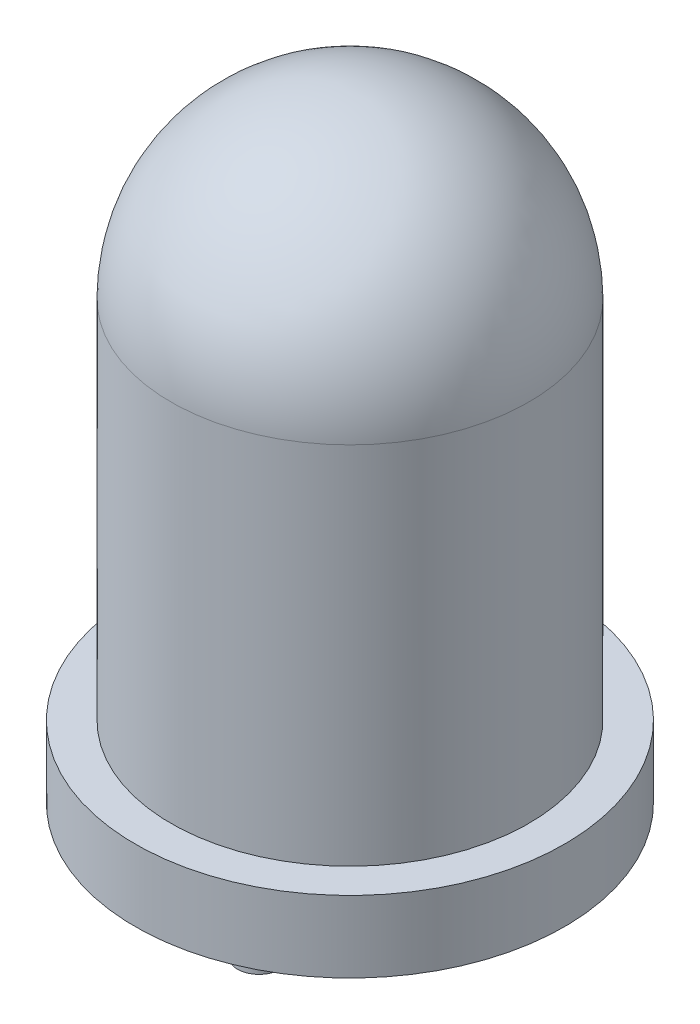
SolidWorks part; units mm, degrees
ref_plane "Plan de face" through (0, 0, 0) normal (0, 0, 1) x (1, 0, 0)
ref_plane "Plan de dessus" through (0, 0, 0) normal (0, 1, 0) x (1, 0, 0)
ref_plane "Plan de droite" through (0, 0, 0) normal (1, 0, 0) x (0, 0, -1)
sketch "Esquisse1" plane through (0, 0, 0) normal (0, 0, 1) x (1, 0, 0)
  line L0 (0, 0) -> (0, 13.8946) construction
  line L1 (-2.5, 6.1) -> (-2.5, 1)
  line L2 (-2.5, 1) -> (-3, 1)
  line L3 (-3, 1) -> (-3, 0)
  line L4 (-3, 0) -> (0, 0)
  line L5 (0, 0) -> (0, 0.5)
  line L6 (-2.2, 6.1) -> (-2.2, 0.5)
  line L7 (-2.2, 0.5) -> (0, 0.5)
  line L8 (0, 8.3) -> (0, 8.6)
  arc A0 (0, 8.6) -> (-2.5, 6.1) centre (0, 6.1) ccw
  arc A1 (0, 8.3) -> (-2.2, 6.1) centre (0, 6.1) ccw
  dimension "D1" = 5
  dimension "D5" = 0.3
  dimension "D2" = 8.6
  dimension "D3" = 6
  dimension "D4" = 1
  dimension "D6" = 0.5
revolve "Révolution1" add sketch "Esquisse1" angle 360 about L0
sketch "Esquisse2" plane through (0, 0, 0) normal (0, -1, 0) x (1, 0, 0)
  line L0 (0, 0) -> (0, 1.7944) construction
  circle A0 centre (-1.27, 0) radius 0.3
  circle A1 centre (1.27, 0) radius 0.3 construction
  dimension "D1" = 2.54
  dimension "D2" = 0.6
extrude "Boss.-Extru.1" add sketch "Esquisse2" along normal blind 2.5
sketch "Esquisse3" plane through (0, 0, 0) normal (0, -1, 0) x (1, 0, 0)
  circle A0 centre (1.27, 0) radius 0.3 construction
  circle A1 centre (1.27, 0) radius 0.3
extrude "Boss.-Extru.2" add sketch "Esquisse3" along normal blind 1
sketch "Esquisse4" plane through (0, 0, 0) normal (0, 0, 1) x (1, 0, 0)
  line L0 (-1.12, 4.2) -> (-0.6104, 2.8)
  line L1 (-1.62, 4.2) -> (-1.12, 4.2)
  line L2 (-1.62, 4.2) -> (-1.62, 0)
  line L3 (-1.62, 0) -> (-0.92, 0)
  line L4 (-0.92, 2.2) -> (-0.92, 0)
  line L5 (-0.6104, 2.8) -> (0.32, 2.8)
  line L6 (0.32, 2.8) -> (0.32, 2.2)
  line L7 (0.32, 2.2) -> (-0.92, 2.2)
  line L8 (-0.6943, 4.2) -> (1.62, 4.2)
  line L9 (1.62, 4.2) -> (1.62, 0)
  line L10 (1.62, 0) -> (0.92, 0)
  line L11 (0.92, 0) -> (0.92, 3.2)
  line L12 (0, 0) -> (0, 1.3747) construction
  line L13 (-0.6943, 4.2) -> (-0.3304, 3.2)
  line L14 (-0.3304, 3.2) -> (0.92, 3.2)
  dimension "D1" = 0.7
  dimension "D2" = 4.2
  dimension "D3" = 0.5
  dimension "D4" = 20
  dimension "D5" = 0.4
  dimension "D6" = 0.6
  dimension "D7" = 0.6
  dimension "D8" = 0.4
  dimension "D9" = 1
extrude "Boss.-Extru.3" add sketch "Esquisse4" along normal mid plane 0.5
sketch "Esquisse5" plane through (0, 4.2, 0) normal (0, 1, 0) x (1, 0, 0)
  circle A0 centre (0, 0) radius 0.6
  dimension "D1" = 1.2
extrude "Boss.-Extru.4" add sketch "Esquisse5" against normal blind 0.2
sketch "Sketch1" plane through (0, 1, 0) normal (0, 1, 0) x (1, 0, 0)
  circle A0 centre (0, 0) radius 2.5 construction
  circle A1 centre (0, 0) radius 2.5
